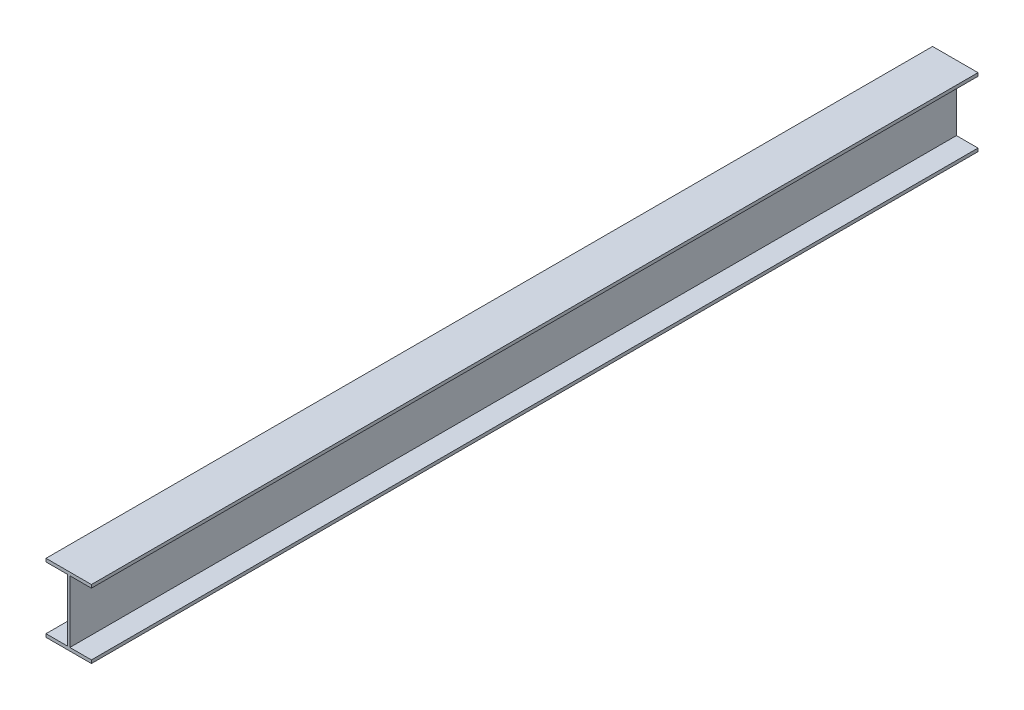
SolidWorks part; units mm, degrees
material "ASTM A992 Steel"
ref_plane "Front" through (0, 0, 0) normal (0, 0, 1) x (1, 0, 0)
ref_plane "Top" through (0, 0, 0) normal (0, 1, 0) x (1, 0, 0)
ref_plane "Right" through (0, 0, 0) normal (1, 0, 0) x (0, 0, -1)
sketch "Sketch1" plane through (0, 0, 0) normal (0, 0, 1) x (1, 0, 0)
  line L0 (0, -0.0002) -> (101.6, -0.0002)
  line L1 (101.6, -0.0002) -> (101.6, -7.1122)
  line L2 (101.6, -7.1122) -> (53.408, -7.1122)
  line L3 (53.408, -7.1122) -> (53.408, -146.0502)
  line L4 (53.408, -146.0502) -> (101.6, -146.0502)
  line L5 (101.6, -146.0502) -> (101.6, -153.1622)
  line L6 (101.6, -153.1622) -> (0, -153.1622)
  line L7 (0, -153.1622) -> (0, -146.0502)
  line L8 (0, -146.0502) -> (47.566, -146.0502)
  line L9 (47.566, -146.0502) -> (47.566, -7.1122)
  line L10 (47.566, -7.1122) -> (0, -7.1122)
  line L11 (0, -7.1122) -> (0, -0.0002)
  line L12 (50.8, -0.0002) -> (50.8, -153.1622) construction
  dimension "D1" = 5.842
  dimension "D2" = 7.112
  dimension "D3" = 7.112
  dimension "D4" = 7.112
  dimension "D5" = 153.162
  dimension "D6" = 50.8
  dimension "D7" = 50.8
  dimension "D8" = 47.566
extrude "Boss-Extrude1" add sketch "Sketch1" along normal blind 1800
sketch "Sketch2" plane through (0, -153.1622, 0) normal (0, -1, 0) x (1, 0, 0)
  line L0 (101.6, 1800) -> (101.6, 0) construction
  line L1 (101.6, 1800) -> (101.6, 0) construction
  line L3 (101.6, 900) -> (101.6, 1050)
  line L4 (101.6, 1050) -> (0, 1050)
  line L5 (0, 900) -> (0, 1050)
  line L6 (0, 1800) -> (0, 0) construction
  line L9 (101.6, 900) -> (101.6, 750)
  line L10 (101.6, 750) -> (0, 750)
  line L11 (0, 900) -> (0, 750)
  point P0 (101.6, 900)
  dimension "D1" = 150
  dimension "D2" = 150
split line "Split Line1"
sketch "Sketch3" plane through (0, 0, 0) normal (0, 0, -1) x (-1, 0, 0)
  line L12 (0, -7.1122) -> (0, -0.0002)
  line L13 (0, -0.0002) -> (-101.6, -0.0002)
  line L14 (-101.6, -0.0002) -> (-101.6, -7.1122)
  line L15 (-101.6, -7.1122) -> (-53.408, -7.1122)
  line L16 (-53.408, -7.1122) -> (-53.408, -146.0502)
  line L17 (-53.408, -146.0502) -> (-101.6, -146.0502)
  line L18 (-101.6, -146.0502) -> (-101.6, -153.1622)
  line L19 (-101.6, -153.1622) -> (0, -153.1622)
  line L20 (0, -153.1622) -> (0, -146.0502)
  line L21 (0, -146.0502) -> (-47.566, -146.0502)
  line L22 (-47.566, -146.0502) -> (-47.566, -7.1122)
  line L23 (-47.566, -7.1122) -> (0, -7.1122)
  line L24 (0, -7.1122) -> (0, -0.0002)
  line L25 (0, -0.0002) -> (-101.6, -0.0002)
  line L26 (-101.6, -0.0002) -> (-101.6, -7.1122)
  line L27 (-101.6, -7.1122) -> (-53.408, -7.1122)
  line L28 (-53.408, -7.1122) -> (-53.408, -146.0502)
  line L29 (-53.408, -146.0502) -> (-101.6, -146.0502)
  line L30 (-101.6, -146.0502) -> (-101.6, -153.1622)
  line L31 (-101.6, -153.1622) -> (0, -153.1622)
  line L32 (0, -153.1622) -> (0, -146.0502)
  line L33 (0, -146.0502) -> (-47.566, -146.0502)
  line L34 (-47.566, -146.0502) -> (-47.566, -7.1122)
  line L35 (-47.566, -7.1122) -> (0, -7.1122)
  dimension "D1" = 0
extrude "Boss-Extrude2" add sketch "Sketch3" along normal blind 183.1
